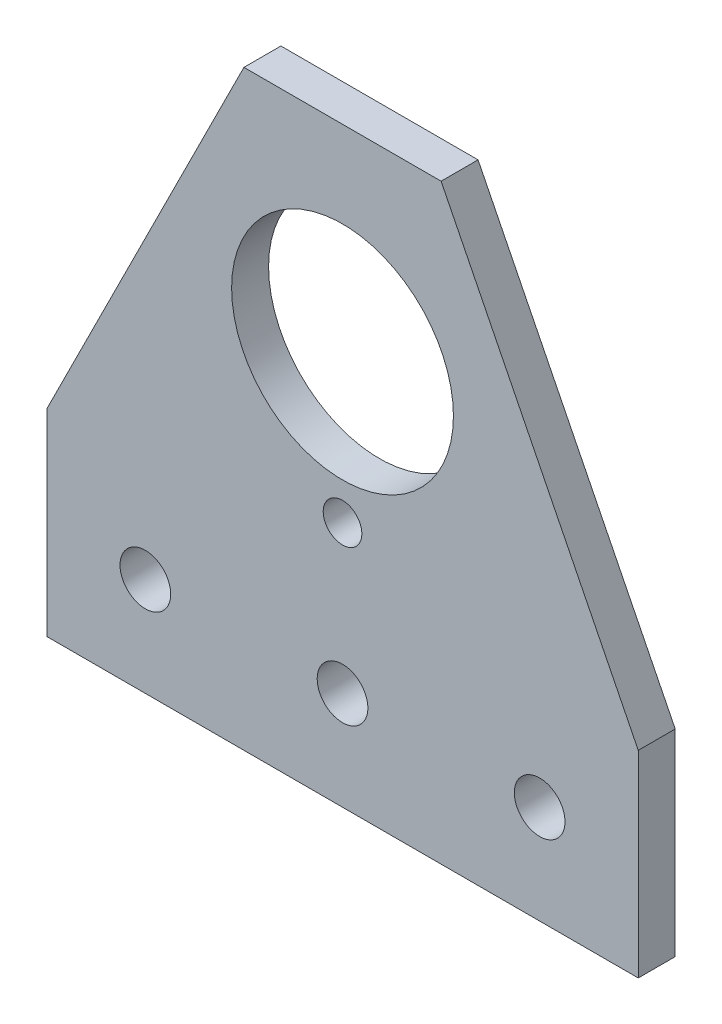
SolidWorks part; units mm, degrees
ref_plane "Front Plane" through (0, 0, 0) normal (0, 0, 1) x (1, 0, 0)
ref_plane "Top Plane" through (0, 0, 0) normal (0, 1, 0) x (1, 0, 0)
ref_plane "Right Plane" through (0, 0, 0) normal (1, 0, 0) x (0, 0, -1)
sketch "Sketch1" plane through (0, 0, 0) normal (0, 0, 1) x (1, 0, 0)
  line L0 (0, 0) -> (76.2, 0)
  line L1 (76.2, 0) -> (76.2, 25.4)
  line L2 (76.2, 25.4) -> (50.8, 76.2)
  line L3 (50.8, 76.2) -> (25.4, 76.2)
  line L4 (25.4, 76.2) -> (0, 25.4)
  line L5 (0, 25.4) -> (0, 0)
  line L6 (38.1, 12.7) -> (63.5, 12.7) construction
  line L7 (38.1, 12.7) -> (38.1, 38.1) construction
  circle A0 centre (38.1, 12.7) radius 3.2639
  circle A1 centre (63.5, 12.7) radius 3.2639
  circle A2 centre (63.5546, 38.1087) radius 3.2639 [skipped]
  circle A3 centre (63.6091, 63.5174) radius 3.2639 [skipped]
  circle A6 centre (12.7, 12.7) radius 3.2639
  circle A7 centre (38.1546, 38.1087) radius 3.2639 [skipped]
  circle A8 centre (38.2091, 63.5174) radius 3.2639 [skipped]
  circle A9 centre (38.1, 50.8) radius 14.2875
  circle A10 centre (38.1, 31.75) radius 2.4892
  dimension "D7" = 6.5278
  dimension "D14" = 6.5278
  dimension "D16" = 28.575
  dimension "D18" = 4.9784
  dimension "D1" = 76.2
  dimension "D2" = 76.2
  dimension "D3" = 25.4
  dimension "D4" = 25.4
  dimension "D5" = 25.4
  dimension "D6" = 12.7
  dimension "D8" = 38.1
  dimension "D11" = 90
  dimension "D12" = 25.4
  dimension "D13" = 25.4
  dimension "D15" = 12.7
  dimension "D17" = 50.8
  dimension "D19" = 31.75
  dimension "D9" = 2
  dimension "D10" = 3
extrude "Boss-Extrude1" add sketch "Sketch1" along normal blind 4.7625
